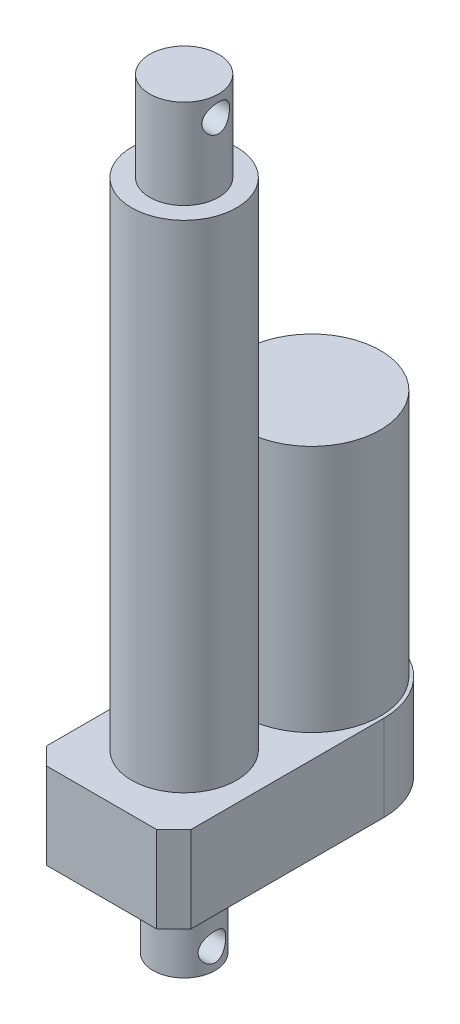
SolidWorks part; units mm, degrees
ref_plane "Front Plane" through (0, 0, 0) normal (0, 0, 1) x (1, 0, 0)
ref_plane "Top Plane" through (0, 0, 0) normal (0, 1, 0) x (1, 0, 0)
ref_plane "Right Plane" through (0, 0, 0) normal (1, 0, 0) x (0, 0, -1)
sketch "Sketch1" plane through (0, 0, 0) normal (0, 1, 0) x (1, 0, 0)
  line L0 (0, -59.1783) -> (0, 67.3408) construction
  line L1 (-16, -24) -> (16, -24)
  line L2 (21, -19) -> (21, 37)
  line L3 (-21, -19) -> (-21, 37)
  line L4 (-49.6024, 58) -> (50.4536, 58) construction
  line L5 (16, -24) -> (21, -19)
  line L6 (-21, -19) -> (-16, -24)
  arc A1 (21, 37) -> (-21, 37) centre (0, 37) ccw
  arc A2 (-21, 37) -> (0, 16) centre (0, 37) ccw construction
  arc A3 (0, 16) -> (21, 37) centre (0, 37) ccw construction
  point P0 (-21, -24)
  point P1 (21, -24)
  dimension "D3" = 82
  dimension "D1" = 24
  dimension "D2" = 42
extrude "Boss-Extrude1" add sketch "Sketch1" along normal blind 25
sketch "Sketch2" plane through (0, 25, 0) normal (0, 1, 0) x (1, 0, 0)
  circle A0 centre (0, 0) radius 15.25
  dimension "D1" = 30.5
extrude "Boss-Extrude2" add sketch "Sketch2" along normal blind 144 contours A0
sketch "Sketch3" plane through (0, 25, 0) normal (0, 1, 0) x (1, 0, 0)
  line L0 (0, -50.4892) -> (0, 100.8473) construction
  arc A0 (21, 37) -> (-21, 37) centre (0, 37) ccw construction
  arc A1 (21, 37) -> (-21, 37) centre (0, 37) ccw construction
  circle A2 centre (0, 37) radius 20
  dimension "D1" = 40
extrude "Boss-Extrude3" add sketch "Sketch3" along normal blind 72
sketch "Sketch4" plane through (0, 0, 0) normal (0, -1, 0) x (1, 0, 0)
  circle A0 centre (0, 0) radius 9
  dimension "D1" = 18
extrude "Boss-Extrude4" add sketch "Sketch4" along normal blind 26
sketch "Sketch5" plane through (0, 0, 0) normal (1, 0, 0) x (0, 0, -1)
  line L0 (-9, -26) -> (9, -26) construction
  line L1 (-9, -26) -> (9, -26) construction
  line L2 (0, 0) -> (0, -26) construction
  line L4 (-19, 0) -> (37, 0) construction
  circle A0 centre (0, -20) radius 4
  dimension "D1" = 8
  dimension "D2" = 20
extrude "Cut-Extrude1" cut sketch "Sketch5" against normal through all both and the other way through all
sketch "Sketch6" plane through (0, 169, 0) normal (0, 1, 0) x (1, 0, 0)
  circle A0 centre (0, 0) radius 10
  dimension "D1" = 20
extrude "Boss-Extrude5" add sketch "Sketch6" along normal blind 26
sketch "Sketch7" plane through (0, 0, 0) normal (1, 0, 0) x (0, 0, -1)
  line L0 (0, -60.5847) -> (0, 265.8364) construction
  circle A0 centre (0, 189) radius 4
  circle A1 centre (0, -20) radius 4 construction
  dimension "D1" = 8
  dimension "D2" = 209
extrude "Cut-Extrude2" cut sketch "Sketch7" against normal through all both and the other way through all
